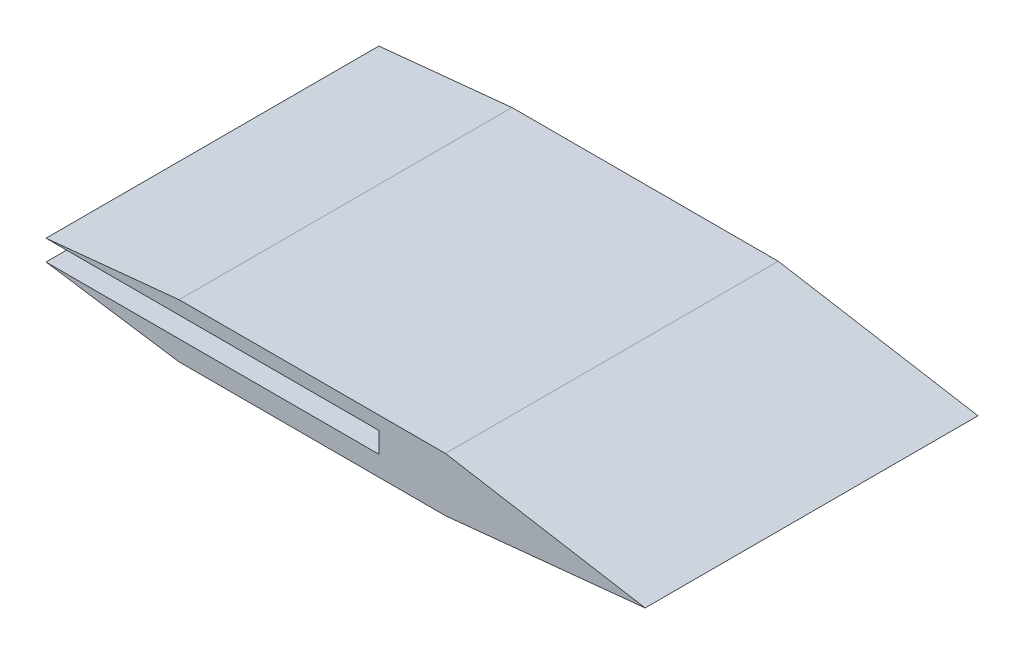
SolidWorks part; units mm, degrees
ref_plane "Přední rovina" through (0, 0, 0) normal (0, 0, 1) x (1, 0, 0)
ref_plane "Horní rovina" through (0, 0, 0) normal (0, 1, 0) x (1, 0, 0)
ref_plane "Pravá rovina" through (0, 0, 0) normal (1, 0, 0) x (0, 0, -1)
sketch "Skica1" plane through (0, 0, 0) normal (0, 0, 1) x (1, 0, 0)
  line L0 (0, 0) -> (20, 2)
  line L1 (20, 2) -> (60, 2)
  line L2 (60, 2) -> (90, -3.1)
  line L3 (90, -3.1) -> (60, -6.1)
  line L6 (0, -3.1) -> (50, -3.1)
  line L7 (50, -3.1) -> (50, 0)
  line L8 (50, 0) -> (0, 0)
  line L9 (50, -3.1) -> (113.4883, -3.1) construction
  line L10 (60, -6.1) -> (20, -6.1)
  line L11 (20, -6.1) -> (0, -3.1)
  point P3 (92.0016, -3.1)
  point P11 (55.2998, -5.6)
  point P12 (93.5979, -3.1)
  point P13 (0, 0)
  point P14 (79.6604, -3.1)
  point P15 (80, -3.1)
  point P16 (95.1476, -3.1)
  dimension "D1" = 3.1
  dimension "D2" = 3
  dimension "D3" = 2
  dimension "D4" = 20
  dimension "D5" = 20
  dimension "D6" = 50
  dimension "D7" = 50
  dimension "D8" = 40
  dimension "D9" = 40
extrude "Přidat vysunutím1" add sketch "Skica1" along normal blind 50
